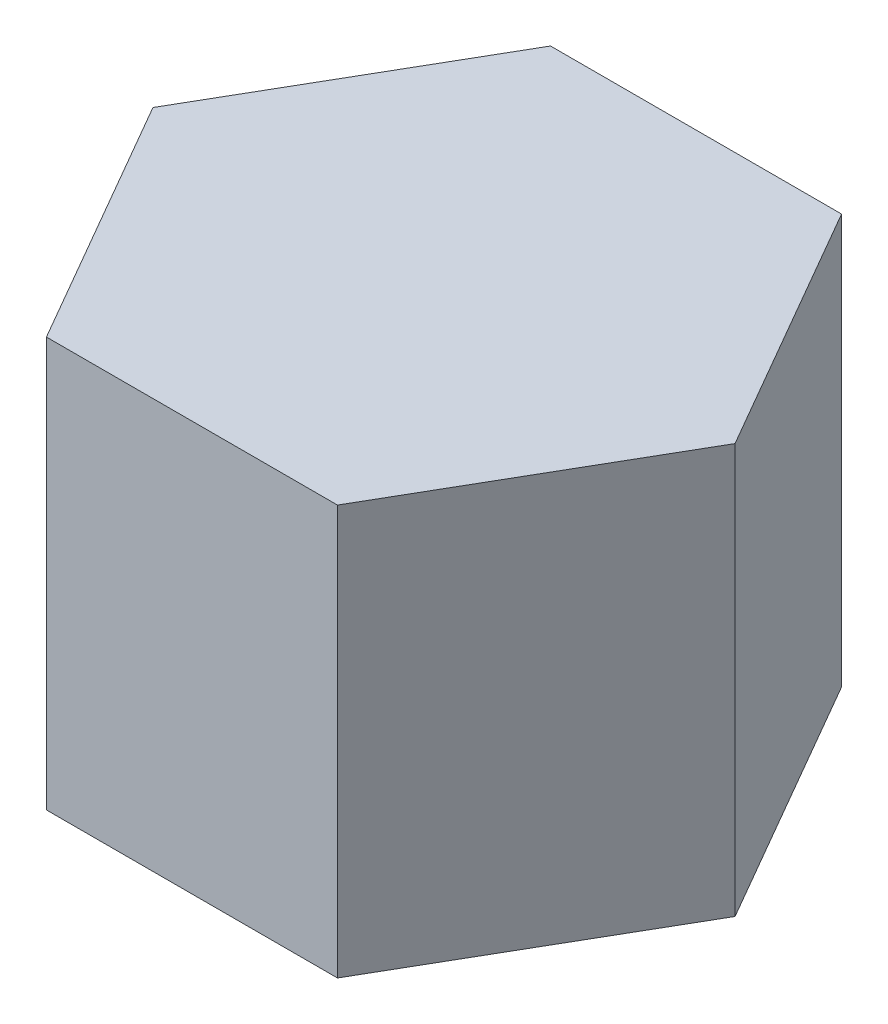
SolidWorks part; units mm, degrees
ref_plane "前视基准面" through (0, 0, 0) normal (0, 0, 1) x (1, 0, 0)
ref_plane "上视基准面" through (0, 0, 0) normal (0, 1, 0) x (1, 0, 0)
ref_plane "右视基准面" through (0, 0, 0) normal (1, 0, 0) x (0, 0, -1)
sketch "草图1" plane through (0, 0, 0) normal (0, 1, 0) x (1, 0, 0)
  line L1 (92.376, 0) -> (46.188, 80)
  line L2 (46.188, 80) -> (-46.188, 80)
  line L3 (-46.188, 80) -> (-92.376, 0)
  line L4 (-92.376, 0) -> (-46.188, -80)
  line L5 (-46.188, -80) -> (46.188, -80)
  line L6 (46.188, -80) -> (92.376, 0)
  circle A0 centre (0, 0) radius 80 construction
  point P1 (69.282, 40)
  dimension "D1" = 80
extrude "凸台-拉伸1" add sketch "草图1" along normal blind 100 and the other way blind 30
